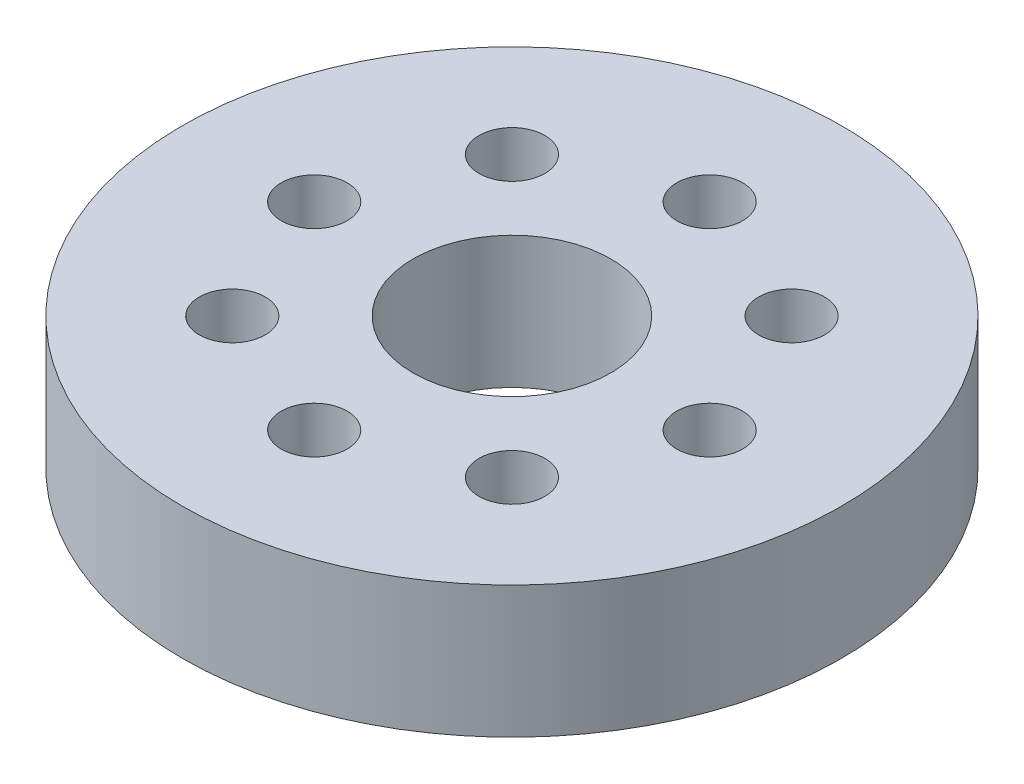
SolidWorks part; units mm, degrees
material "ABS"
ref_plane "Front Plane" through (0, 0, 0) normal (0, 0, 1) x (1, 0, 0)
ref_plane "Top Plane" through (0, 0, 0) normal (0, 1, 0) x (1, 0, 0)
ref_plane "Right Plane" through (0, 0, 0) normal (1, 0, 0) x (0, 0, -1)
sketch "Sketch2" plane through (0, 0, 0) normal (0, 1, 0) x (1, 0, 0)
  line L0 (-10.9846, 0) -> (11.4312, 0) construction
  line L1 (0, 4.5811) -> (0, -5.6811) construction
  circle A0 centre (0, 0) radius 10
  circle A1 centre (0, 0) radius 3
  circle A2 centre (0, 6) radius 1
  circle A3 centre (4.2426, 4.2426) radius 1
  circle A4 centre (6, 0) radius 1
  circle A5 centre (4.2426, -4.2426) radius 1
  circle A6 centre (0, -6) radius 1
  circle A7 centre (-4.2426, -4.2426) radius 1
  circle A8 centre (-6, 0) radius 1
  circle A9 centre (-4.2426, 4.2426) radius 1
  point P27 (0, 0)
  dimension "D1" = 20
  dimension "D2" = 6
  dimension "D4" = 2
  dimension "D3" = 6
  dimension "D5" = 8
extrude "Boss-Extrude1" add sketch "Sketch2" along normal blind 4
